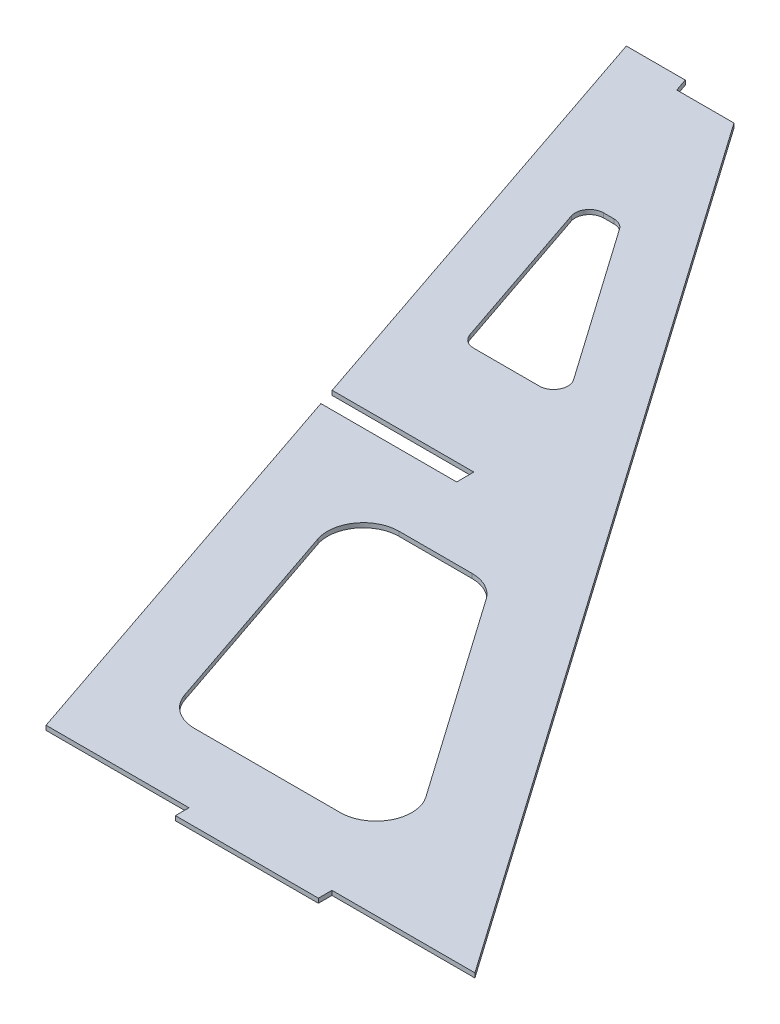
SolidWorks part; units mm, degrees
material "Balsa"
ref_plane "Front Plane" through (0, 0, 0) normal (0, 0, 1) x (1, 0, 0)
ref_plane "Top Plane" through (0, 0, 0) normal (0, 1, 0) x (1, 0, 0)
ref_plane "Right Plane" through (0, 0, 0) normal (1, 0, 0) x (0, 0, -1)
sketch "Sketch1" plane through (0, 0, 0) normal (0, 1, 0) x (1, 0, 0)
  line L2 (-207.5367, 316.9621) -> (-186.5817, 316.9621)
  line L3 (-186.5817, 316.9621) -> (-185.0307, 312.3921)
  line L4 (-185.0307, 312.3921) -> (-164.7107, 312.3921)
  line L5 (-164.7107, 312.3921) -> (50.8, 4.826)
  line L6 (50.8, 4.826) -> (0, 4.826)
  line L7 (0, 4.826) -> (0, 0)
  line L8 (0, 0) -> (-50.8, 0)
  line L9 (-50.8, 0) -> (-50.8, 4.826)
  line L10 (-50.8, 4.826) -> (-101.6, 4.826)
  line L11 (-101.6, 4.826) -> (-207.5367, 316.9621)
  point P1 (53.34, 4.826)
  dimension "D1" = 108.747
  dimension "D2" = 20.32
  dimension "D3" = 20.955
  dimension "D4" = 50.8
  dimension "D6" = 50.8
  dimension "D7" = 50.8
  dimension "D8" = 4.826
  dimension "D9" = 4.826
extrude "Boss-Extrude1" add sketch "Sketch1" along normal blind 1.5875
sketch "Sketch2" plane through (0, 1.5875, 0) normal (0, 1, 0) x (1, 0, 0)
  line L4 (-103.5117, 158.75) -> (-103.5117, 152.654)
  line L6 (-103.5117, 152.654) -> (-151.7717, 152.654)
  line L7 (-207.5367, 316.9621) -> (-101.6, 4.826) construction
  line L8 (-151.7717, 152.654) -> (-153.8407, 158.75)
  line L9 (-153.8407, 158.75) -> (-103.5117, 158.75)
  line L10 (-50.8, 0) -> (0, 0) construction
  dimension "D1" = 158.75
  dimension "D2" = 48.26
  dimension "D3" = 6.096
extrude "Cut-Extrude1" cut sketch "Sketch2" against normal through all
sketch "Sketch3" plane through (0, 1.5875, 0) normal (0, 1, 0) x (1, 0, 0)
  line L0 (-116.3281, 127.254) -> (-83.3976, 30.226)
  line L1 (-83.3976, 30.226) -> (1.9875, 30.226)
  line L2 (1.9875, 30.226) -> (-65.9997, 127.254)
  line L3 (-65.9997, 127.254) -> (-116.3281, 127.254)
  line L4 (-167.2861, 261.5921) -> (-145.3131, 196.85)
  line L5 (-145.3131, 196.85) -> (-108.5625, 196.85)
  line L6 (-108.5625, 196.85) -> (-153.9271, 261.5921)
  line L7 (-153.9271, 261.5921) -> (-167.2861, 261.5921)
  line L8 (-207.5367, 316.9621) -> (-153.8407, 158.75) construction
  line L9 (-103.5117, 158.75) -> (-153.8407, 158.75) construction
  line L10 (50.8, 4.826) -> (-164.7107, 312.3921) construction
  line L11 (-101.6, 4.826) -> (-50.8, 4.826) construction
  line L12 (-151.7717, 152.654) -> (-101.6, 4.826) construction
  line L13 (-151.7717, 152.654) -> (-101.6, 4.826) construction
  line L14 (-151.7717, 152.654) -> (-103.5117, 152.654) construction
  line L15 (-207.5367, 316.9621) -> (-153.8407, 158.75) construction
  line L16 (-164.7107, 312.3921) -> (-185.0307, 312.3921) construction
  dimension "D1" = 25.4
  dimension "D2" = 25.4
  dimension "D3" = 25.4
  dimension "D4" = 25.4
  dimension "D5" = 38.1
  dimension "D6" = 20.32
  dimension "D7" = 20.32
  dimension "D8" = 50.8
extrude "Cut-Extrude2" cut sketch "Sketch3" against normal through all
fillet "Fillet1" radius 12.7 4 edges at (1.9875, 0.7937, -30.226) (-83.3976, 0.7937, -30.226) (-65.9997, 0.7937, -127.254) (-116.3281, 0.7937, -127.254)
fillet "Fillet2" radius 5.08 4 edges at (-108.5625, 0.7937, -196.85) (-145.3131, 0.7937, -196.85) (-153.9271, 0.7937, -261.5921) (-167.2861, 0.7937, -261.5921)
